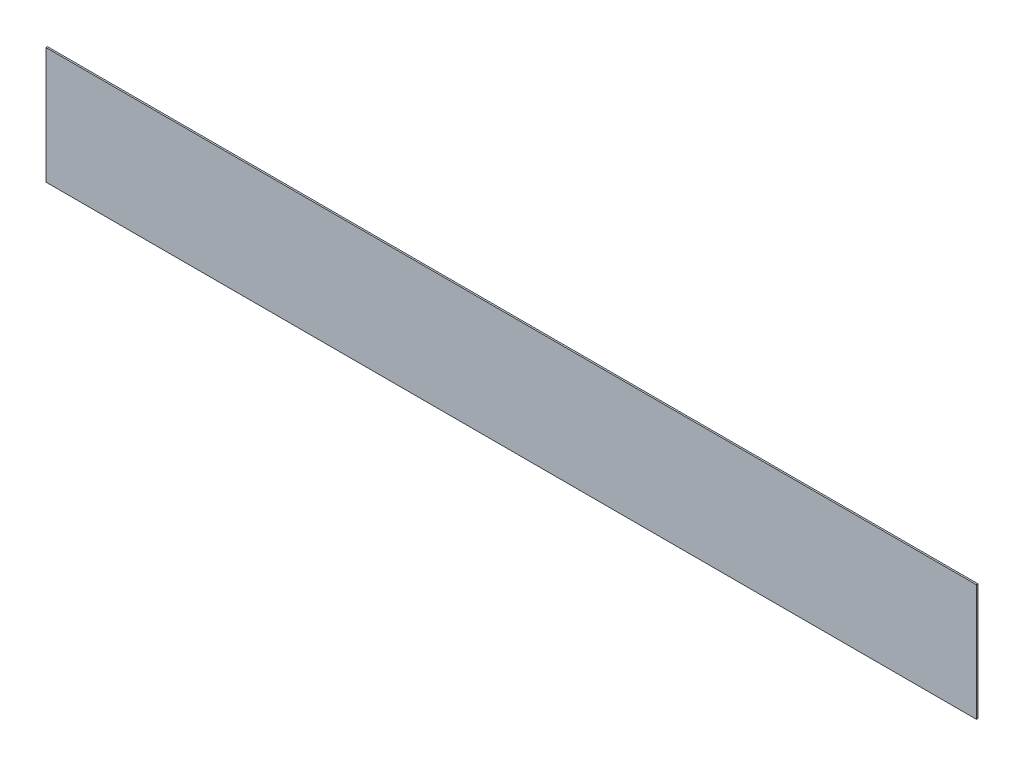
SolidWorks part; units mm, degrees
ref_plane "Front Plane" through (0, 0, 0) normal (0, 0, 1) x (1, 0, 0)
ref_plane "Top Plane" through (0, 0, 0) normal (0, 1, 0) x (1, 0, 0)
ref_plane "Right Plane" through (0, 0, 0) normal (1, 0, 0) x (0, 0, -1)
other "Configuration Table"
sketch "Sketch1" plane through (0, 0, 0) normal (0, 0, 1) x (1, 0, 0)
  line L1 (13.7, 8) -> (604.3, 8)
  line L2 (13.7, 8) -> (13.7, 82)
  line L3 (13.7, 82) -> (604.3, 82)
  line L4 (604.3, 8) -> (604.3, 82)
extrude "CEK_donmus_kutu_arka_1.0_1" add sketch "Sketch1" against normal blind 1 from offset 699 separate body
